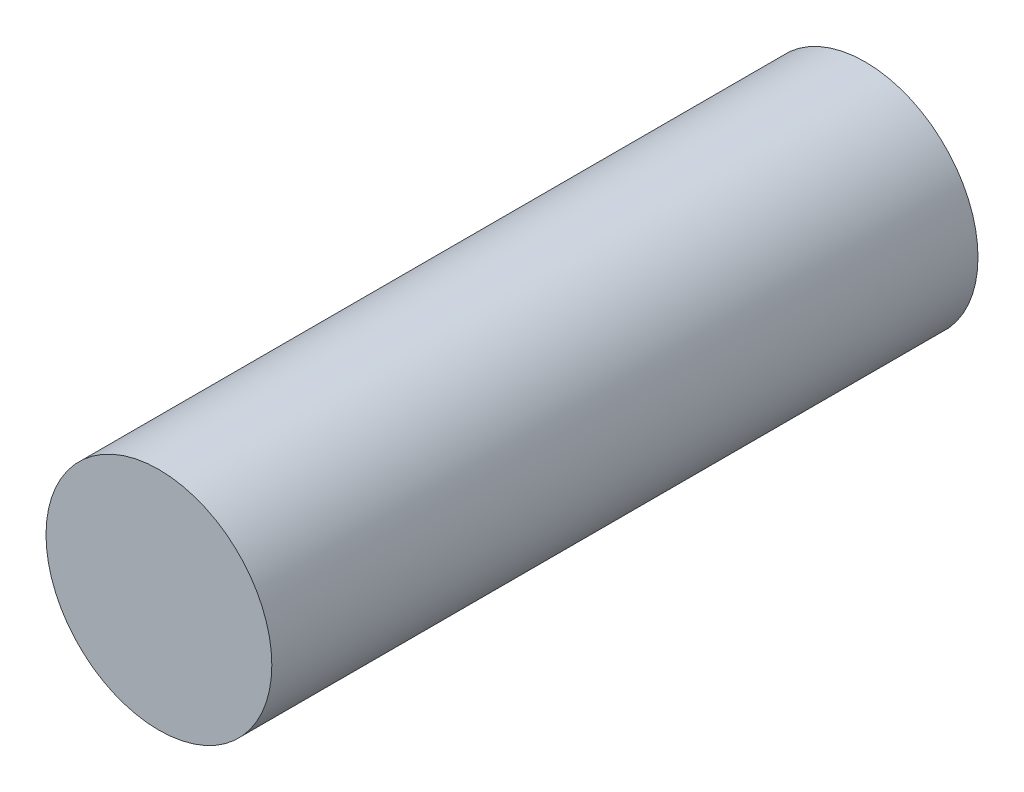
SolidWorks part; units mm, degrees
ref_plane "Front Plane" through (0, 0, 0) normal (0, 0, 1) x (1, 0, 0)
ref_plane "Top Plane" through (0, 0, 0) normal (0, 1, 0) x (1, 0, 0)
ref_plane "Right Plane" through (0, 0, 0) normal (1, 0, 0) x (0, 0, -1)
sketch "Sketch1" plane through (0, 0, 0) normal (0, 0, 1) x (1, 0, 0)
  circle A0 centre (0, 0) radius 1.9939
  dimension "D1" = 3.9878
extrude "Boss-Extrude1" add sketch "Sketch1" along normal mid plane 12.4714
